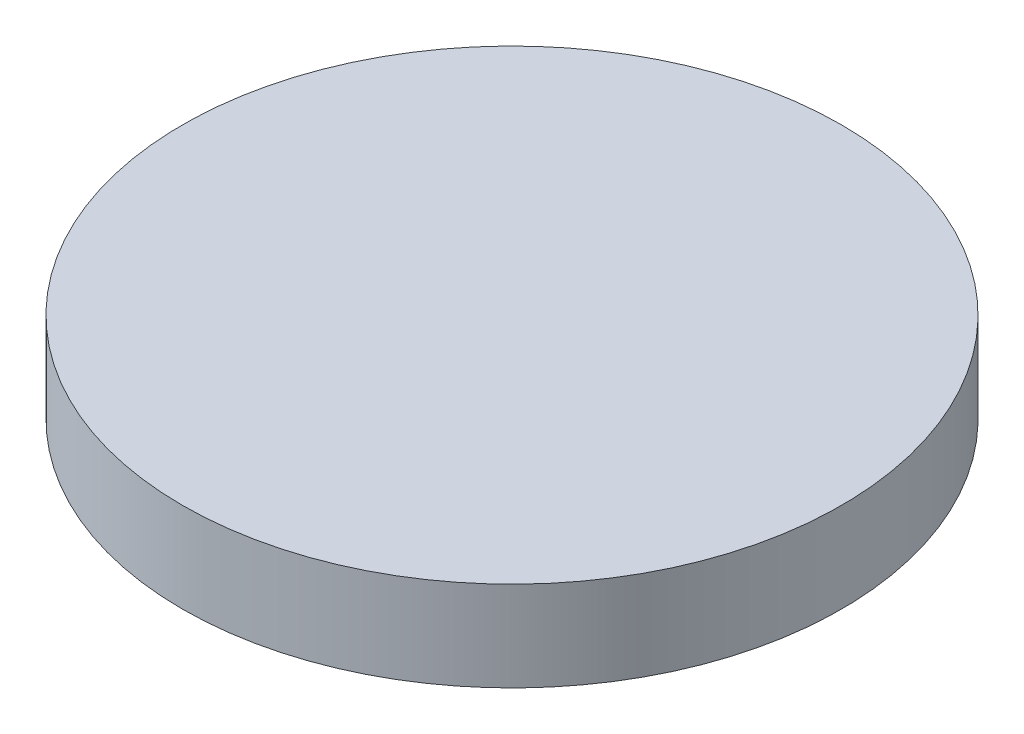
SolidWorks part; units mm, degrees
ref_plane "Front Plane" through (0, 0, 0) normal (0, 0, 1) x (1, 0, 0)
ref_plane "Top Plane" through (0, 0, 0) normal (0, 1, 0) x (1, 0, 0)
ref_plane "Right Plane" through (0, 0, 0) normal (1, 0, 0) x (0, 0, -1)
sketch "Sketch1" plane through (0, 0, 0) normal (0, 1, 0) x (1, 0, 0)
  circle A0 centre (0, 0) radius 69.85
  dimension "D1" = 139.7
extrude "Boss-Extrude1" add sketch "Sketch1" along normal blind 19.05
